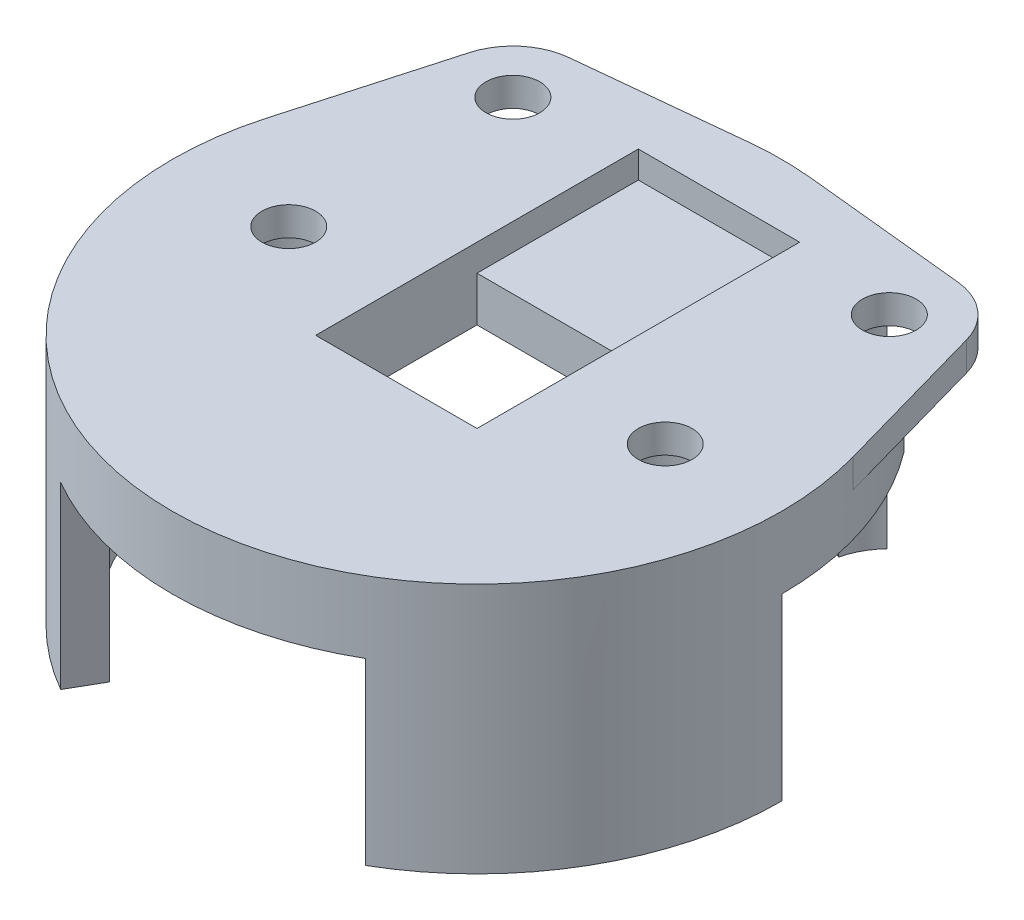
SolidWorks part; units mm, degrees
ref_plane "Front Plane" through (0, 0, 0) normal (0, 0, 1) x (1, 0, 0)
ref_plane "Top Plane" through (0, 0, 0) normal (0, 1, 0) x (1, 0, 0)
ref_plane "Right Plane" through (0, 0, 0) normal (1, 0, 0) x (0, 0, -1)
sketch "Sketch1" plane through (0, 0, 0) normal (0, 1, 0) x (1, 0, 0)
  circle A0 centre (0, 0) radius 15
  circle A1 centre (0, 0) radius 17
  dimension "D1" = 30
  dimension "D2" = 2
extrude "Boss-Extrude1" add sketch "Sketch1" against normal blind 10
sketch "Sketch5" plane through (0, 0, 0) normal (0, 1, 0) x (1, 0, 0)
  line L0 (-5.5, 0) -> (5.5, 0) construction
  line L1 (0, -5.5) -> (0, 5.5) construction
  line L2 (-10.8548, 15.982) -> (-1.7233, 16.9124)
  line L3 (-13.8685, 13.4505) -> (-16.3611, 4.6167)
  line L4 (1.7233, 16.9124) -> (10.8548, 15.982)
  line L5 (13.8685, 13.4505) -> (16.3611, 4.6167)
  line L7 (-4.5, -4.5) -> (4.5, -4.5)
  line L8 (-4.5, -4.5) -> (-4.5, 4.5)
  line L9 (-4.5, 4.5) -> (4.5, 4.5)
  line L10 (4.5, -4.5) -> (4.5, 4.5)
  line L11 (-4.5, -4.5) -> (4.5, 4.5) construction
  line L12 (-4.5, 4.5) -> (4.5, -4.5) construction
  circle A0 centre (-10.5, 0) radius 1.5
  circle A1 centre (10.5, 0) radius 1.5
  circle A2 centre (-10.5, 12.5) radius 1.5
  circle A3 centre (10.5, 12.5) radius 1.5
  arc A4 (-16.3611, 4.6167) -> (16.3611, 4.6167) centre (0, 0) ccw
  circle A5 centre (0, 0) radius 17 construction
  arc A6 (13.8685, 13.4505) -> (10.8548, 15.982) centre (10.5, 12.5) ccw
  arc A7 (-10.8548, 15.982) -> (-13.8685, 13.4505) centre (-10.5, 12.5) ccw
  arc A10 (1.7233, 16.9124) -> (-1.7233, 16.9124) centre (0, 0) ccw
  dimension "D1" = 10.5
  dimension "D3" = 12.5
  dimension "D4" = 2
  dimension "D5" = 2
  dimension "D7" = 3
  dimension "D2" = 10.5
  dimension "D8" = 9
extrude "Boss-Extrude2" add sketch "Sketch5" along normal blind 4
sketch "Sketch9" plane through (0, 0, 0) normal (0, -1, 0) x (1, 0, 0)
  line L0 (0, 0) -> (-14.7097, -8.4926) construction
  line L1 (0, 0) -> (14.7097, -8.4926) construction
  line L2 (7.5, 12.9904) -> (8.5, 14.7224)
  line L3 (7.5, -12.9904) -> (8.5, -14.7224)
  line L4 (-7.5, -12.9904) -> (-8.5, -14.7224)
  line L5 (-15, 0) -> (-17, 0)
  line L6 (15, 0) -> (17, 0)
  line L7 (-7.5, 12.9904) -> (-8.5, 14.7224)
  line L8 (0, -5.5) -> (0, 5.5) construction
  circle A0 centre (0, 0) radius 17 construction
  arc A1 (7.5, 12.9904) -> (-7.5, 12.9904) centre (0, 0) ccw
  arc A2 (8.5, 14.7224) -> (-8.5, 14.7224) centre (0, 0) ccw
  arc A3 (-17, 0) -> (-8.5, -14.7224) centre (0, 0) ccw
  arc A4 (-15, 0) -> (-7.5, -12.9904) centre (0, 0) ccw
  arc A5 (7.5, -12.9904) -> (15, 0) centre (0, 0) ccw
  arc A6 (8.5, -14.7224) -> (17, 0) centre (0, 0) ccw
  dimension "D1" = 30
  dimension "D2" = 30
  dimension "D3" = 30
  dimension "D4" = 30
  dimension "D5" = 60
  dimension "D6" = 60
  dimension "D7" = 30
  dimension "D8" = 30
extrude "Cut-Extrude2" cut sketch "Sketch9" along normal up to next
sketch "Sketch10" plane through (0, 0, 0) normal (0, -1, 0) x (1, 0, 0)
  line L0 (-13.8685, -13.4505) -> (-16.3611, -4.6167)
  line L3 (13.8685, -13.4505) -> (16.3611, -4.6167)
  line L4 (10.8548, -15.982) -> (1.7233, -16.9124)
  line L5 (-10.8548, -15.982) -> (-1.7233, -16.9124)
  arc A0 (-7.7552, -15.128) -> (-13.5623, -10.2501) centre (-10.5, -12.5) ccw
  arc A1 (13.5623, -10.2501) -> (7.7552, -15.128) centre (10.5, -12.5) ccw
  circle A2 centre (-10.5, 0) radius 3.45
  circle A3 centre (10.5, 0) radius 3.45
  arc A4 (-16.3611, -4.6167) -> (-13.5623, -10.2501) centre (0, 0) ccw
  arc A5 (13.5623, -10.2501) -> (16.3611, -4.6167) centre (0, 0) ccw
  arc A6 (-7.7552, -15.128) -> (7.7552, -15.128) centre (0, 0) ccw
  arc A7 (-13.8685, -13.4505) -> (-10.8548, -15.982) centre (-10.5, -12.5) ccw
  arc A8 (10.8548, -15.982) -> (13.8685, -13.4505) centre (10.5, -12.5) ccw
  arc A9 (-13.8685, -13.4505) -> (-10.8548, -15.982) centre (-10.5, -12.5) ccw construction
  arc A10 (16.3611, -4.6167) -> (-16.3611, -4.6167) centre (0, 0) ccw construction
  circle M1 centre (-10.5, -12.5) radius 1.5
  line M2 (7.5, -12.9904) -> (8.5, -14.7224)
  arc M3 (8.5, -14.7224) -> (1.7233, -16.9124) centre (0, 0) cw
  line M4 (1.7233, -16.9124) -> (10.8548, -15.982)
  arc M5 (10.8548, -15.982) -> (13.8685, -13.4505) centre (10.5, -12.5) ccw
  line M6 (13.8685, -13.4505) -> (16.3611, -4.6167)
  line M16 (-16.3611, -4.6167) -> (-13.8685, -13.4505)
  arc M17 (-13.8685, -13.4505) -> (-10.8548, -15.982) centre (-10.5, -12.5) ccw
  line M18 (-10.8548, -15.982) -> (-1.7233, -16.9124)
  arc M19 (-1.7233, -16.9124) -> (-8.5, -14.7224) centre (0, 0) cw
  line M20 (-8.5, -14.7224) -> (-7.5, -12.9904)
  arc M21 (-7.5, -12.9904) -> (7.5, -12.9904) centre (0, 0) ccw
  circle M22 centre (10.5, -12.5) radius 1.5
  circle M23 centre (10.5, 0) radius 1.5
  circle M24 centre (-10.5, 0) radius 1.5
  dimension "D1" = 7.6
  dimension "D2" = 6.9
extrude "Cut-Extrude3" cut sketch "Sketch10" against normal blind 2.4 and the other way through all contours A5 A1 M2 M3 M4 M5 M6 M22 | A3 M23 | A2 M24 | A4 A0 M16 M17 M18 M19 M20 M1 | A1 M21 M3 M2 | A0 M19 M21 M20
sketch "Sketch11" plane through (0, 4, 0) normal (0, 1, 0) x (1, 0, 0)
  line L0 (4.5, 4.5) -> (-4.5, 4.5) construction
  line L1 (-4.5, 4.5) -> (4.5, 4.5)
  line L2 (-4.5, 4.5) -> (-4.5, 13.5)
  line L3 (-4.5, 13.5) -> (4.5, 13.5)
  line L4 (4.5, 4.5) -> (4.5, 13.5)
  line L5 (0, -8.4168) -> (0, 15.3607) construction
  dimension "D1" = 9
  dimension "D2" = 9
extrude "Cut-Extrude4" cut sketch "Sketch11" against normal blind 1.5
